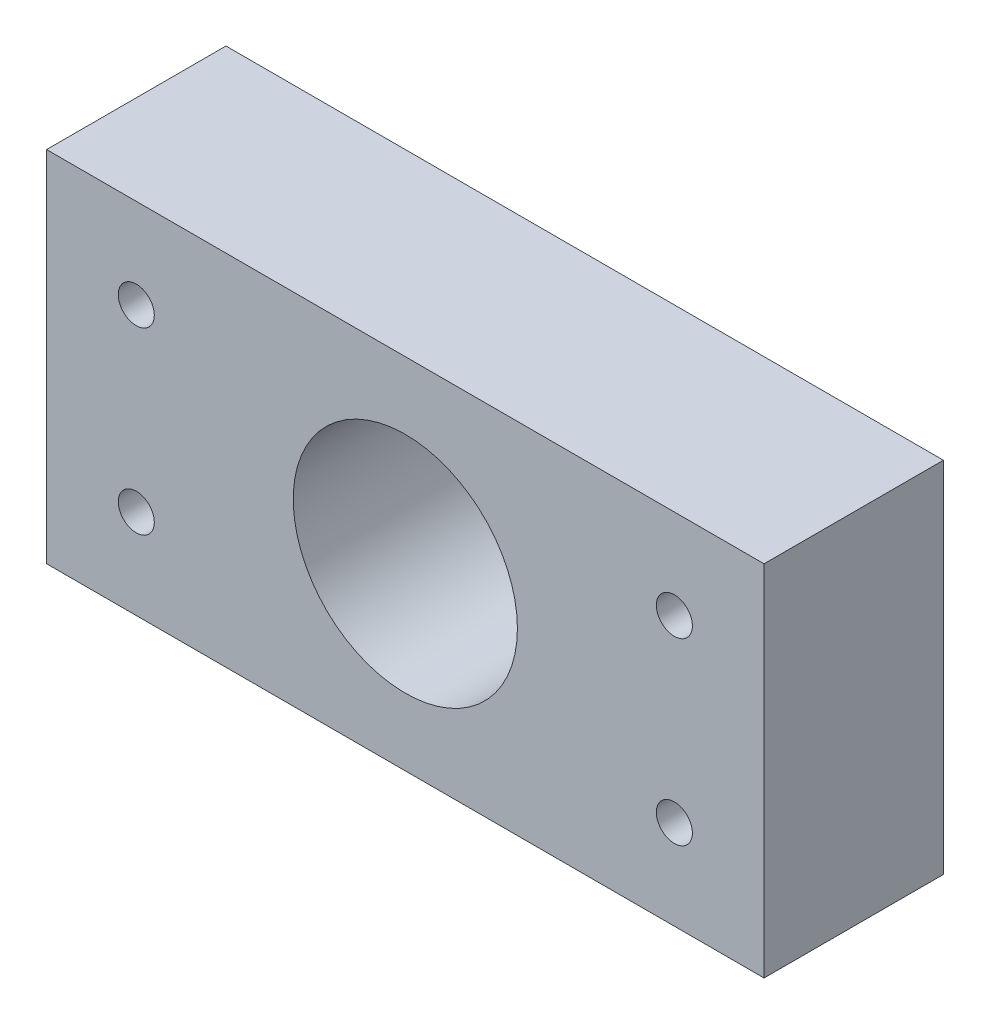
SolidWorks part; units mm, degrees
ref_plane "Front" through (0, 0, 0) normal (0, 0, 1) x (1, 0, 0)
ref_plane "Top" through (0, 0, 0) normal (0, 1, 0) x (1, 0, 0)
ref_plane "Right" through (0, 0, 0) normal (1, 0, 0) x (0, 0, -1)
sketch "Sketch1" plane through (0, 0, 0) normal (0, 1, 0) x (1, 0, 0)
  line L1 (-50.8, -12.7) -> (50.8, -12.7)
  line L2 (-50.8, -12.7) -> (-50.8, 12.7)
  line L3 (-50.8, 12.7) -> (50.8, 12.7)
  line L4 (50.8, -12.7) -> (50.8, 12.7)
  line L5 (-50.8, -12.7) -> (50.8, 12.7) construction
  line L6 (-50.8, 12.7) -> (50.8, -12.7) construction
  point P0 (0, 0)
  dimension "D1" = 101.6
  dimension "D2" = 25.4
extrude "Boss-Extrude1" add sketch "Sketch1" along normal mid plane 50.8 contours L3 L4 L1 L2
sketch "Sketch2" plane through (0, 0, 12.7) normal (0, 0, 1) x (1, 0, 0)
  circle A0 centre (0, 0) radius 15.875
  dimension "D1" = 31.75
extrude "Cut-Extrude1" cut sketch "Sketch2" against normal up to next contours A0
sketch "Sketch3" plane through (0, 0, 12.7) normal (0, 0, 1) x (1, 0, 0)
  line L0 (50.8, 25.4) -> (50.8, -25.4) construction
  line L1 (-38.1, -12.7) -> (-38.1, 12.7) construction
  line L2 (-38.1, 12.7) -> (38.1, 12.7) construction
  line L3 (50, 0) -> (-50, 0) construction
  line L4 (0, -50) -> (0, 50) construction
  point P0 (-38.1, 12.7)
  point P1 (-38.1, -12.7)
  point P2 (38.1, 12.7)
  point P3 (38.1, -12.7)
  point P5 (-38.1, 0)
  point P12 (0, 12.7)
  dimension "D1" = 12.7
  dimension "D2" = 25.4
hole_wizard "1/4-20 Tapped Hole1" positions "Sketch4" profile "Sketch5" tap size "1/4-20" standard "ANSI Inch" end condition through all
sketch "Sketch4" plane through (0, 0, 12.7) normal (0, 0, 1) x (1, 0, 0)
  point P0 (-38.1, 12.7)
  point P3 (-38.1, -12.7)
  point P6 (38.1, 12.7)
  point P9 (38.1, -12.7)
sketch "Sketch5" plane through (-38.1, 12.7, 12.7) normal (1, 0, 0) x (0, -1, 0)
  line L0 (0, 0) -> (0, 25.4)
  line L1 (0, 25.4) -> (2.5527, 25.4)
  line L2 (2.5527, 25.4) -> (2.5527, 0)
  line L5 (2.5527, 0) -> (0, 0)
  line L11 (0, -6.35) -> (0, 107.95) construction
  dimension "Thru Tap Drill Dia." = 5.1054
  dimension "Thru Tap Drill Depth" = 25.4
